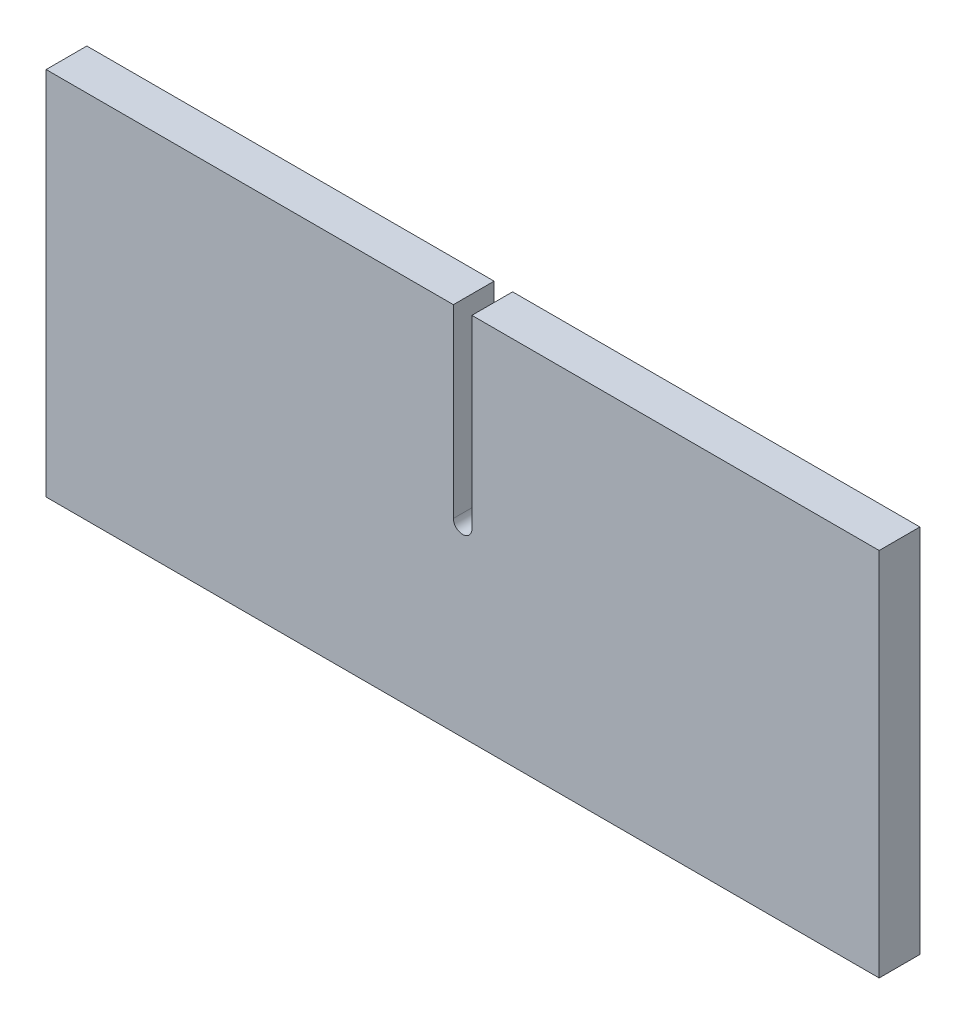
SolidWorks part; units mm, degrees
ref_plane "Plan de face" through (0, 0, 0) normal (0, 0, 1) x (1, 0, 0)
ref_plane "Plan de dessus" through (0, 0, 0) normal (0, 1, 0) x (1, 0, 0)
ref_plane "Plan de droite" through (0, 0, 0) normal (1, 0, 0) x (0, 0, -1)
sketch "Esquisse1" plane through (0, 0, 0) normal (0, 0, 1) x (1, 0, 0)
  line L0 (-225, 100) -> (-5, 100)
  line L1 (225, -100) -> (-225, -100)
  line L2 (225, -100) -> (225, 100)
  line L4 (-225, -100) -> (-225, 100)
  line L5 (225, -100) -> (-225, 100) construction
  line L6 (225, 100) -> (-225, -100) construction
  line L7 (225, 100) -> (5, 100)
  line L8 (-5, 100) -> (-5, 0)
  line L9 (5, 100) -> (5, 0)
  arc A0 (-5, 0) -> (5, 0) centre (0, 0) ccw
  point P0 (0, 0)
  dimension "D1" = 200
  dimension "D2" = 450
  dimension "D3" = 220
  dimension "D4" = 220
extrude "Boss.-Extru.1" add sketch "Esquisse1" along normal blind 22
